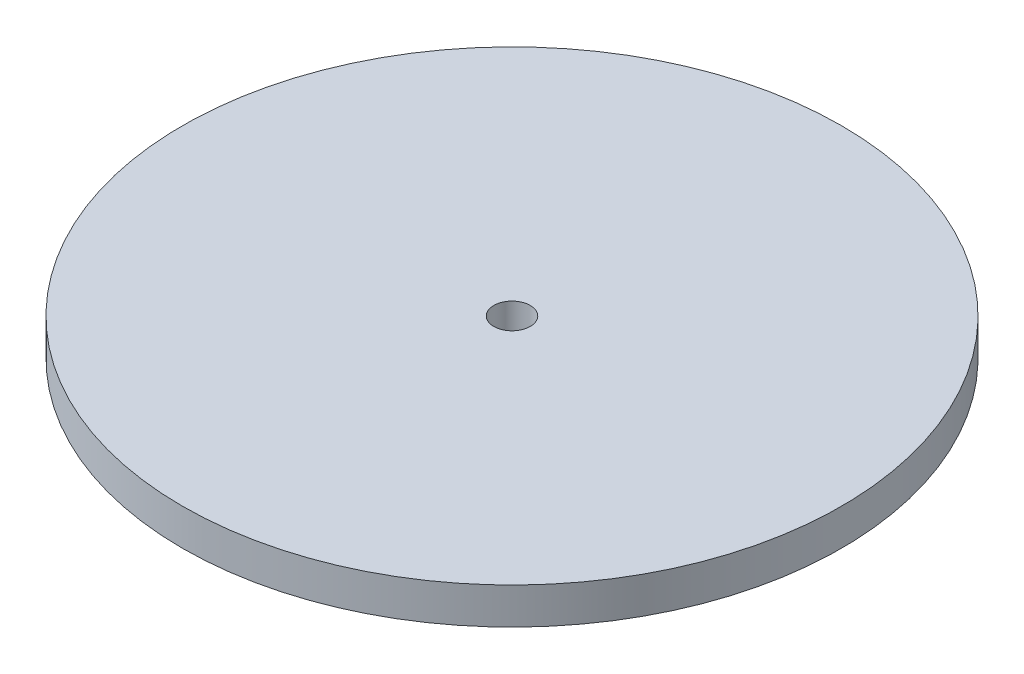
SolidWorks part; units mm, degrees
ref_plane "Front Plane" through (0, 0, 0) normal (0, 0, 1) x (1, 0, 0)
ref_plane "Top Plane" through (0, 0, 0) normal (0, 1, 0) x (1, 0, 0)
ref_plane "Right Plane" through (0, 0, 0) normal (1, 0, 0) x (0, 0, -1)
sketch "Sketch1" plane through (0, 0, 0) normal (0, 1, 0) x (1, 0, 0)
  circle A0 centre (0, 0) radius 36.15
  circle A1 centre (0, 0) radius 2
  dimension "D1" = 72.3
  dimension "D2" = 4
extrude "Boss-Extrude1" add sketch "Sketch1" along normal blind 4
